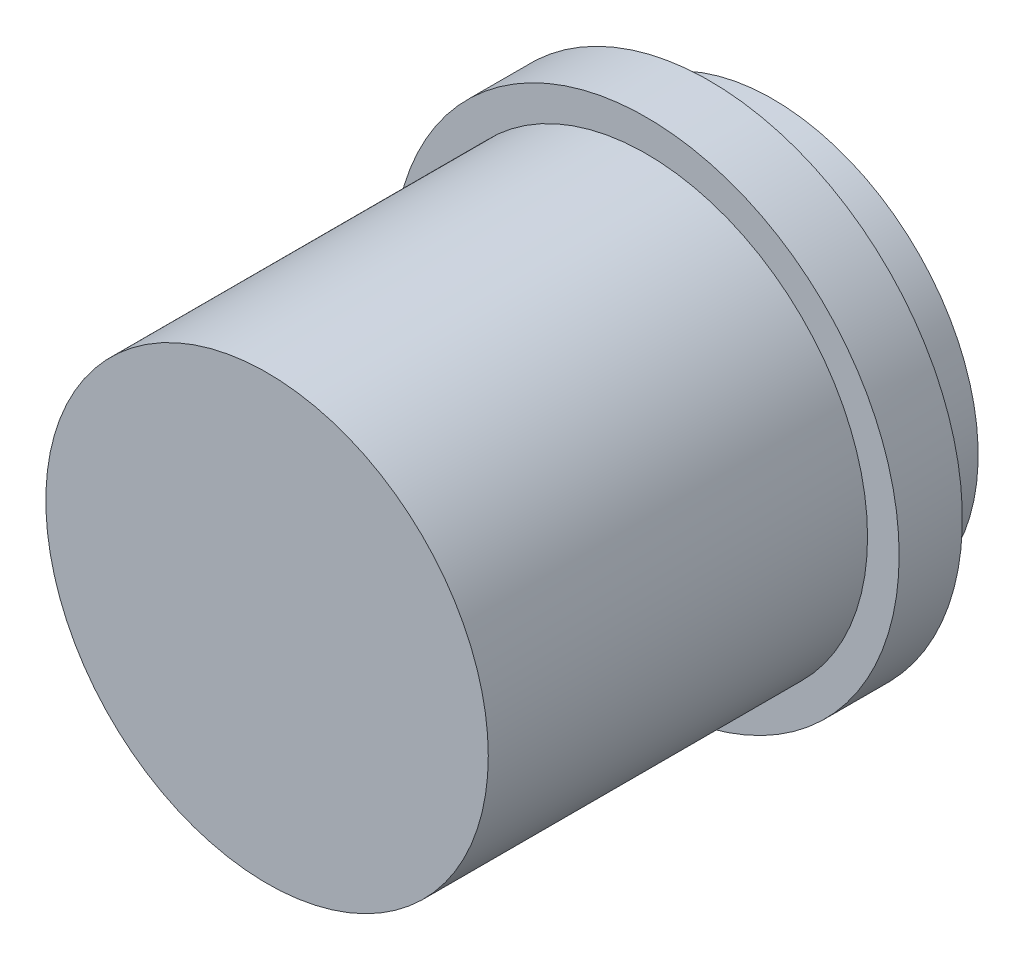
SolidWorks part; units mm, degrees
ref_plane "Płaszczyzna przednia" through (0, 0, 0) normal (0, 0, 1) x (1, 0, 0)
ref_plane "Płaszczyzna górna" through (0, 0, 0) normal (0, 1, 0) x (1, 0, 0)
ref_plane "Płaszczyzna prawa" through (0, 0, 0) normal (1, 0, 0) x (0, 0, -1)
sketch "Szkic1" plane through (0, 0, 0) normal (0, 0, 1) x (1, 0, 0)
  circle A0 centre (0, 0) radius 8
extrude "Dodanie-wyciągnięcie1" add sketch "Szkic1" along normal blind 16
sketch "Szkic2" plane through (0, 0, 16) normal (0, 0, 1) x (1, 0, 0)
  circle A0 centre (0, 0) radius 7
  circle A1 centre (0, 0) radius 8
extrude "Wytnij-wyciągnięcie1" cut sketch "Szkic2" against normal blind 12
sketch "Szkic3" plane through (0, 0, 0) normal (0, 0, -1) x (-1, 0, 0)
  circle A0 centre (0, 0) radius 6.5
  circle A1 centre (0, 0) radius 8
extrude "Wytnij-wyciągnięcie2" cut sketch "Szkic3" against normal blind 2
